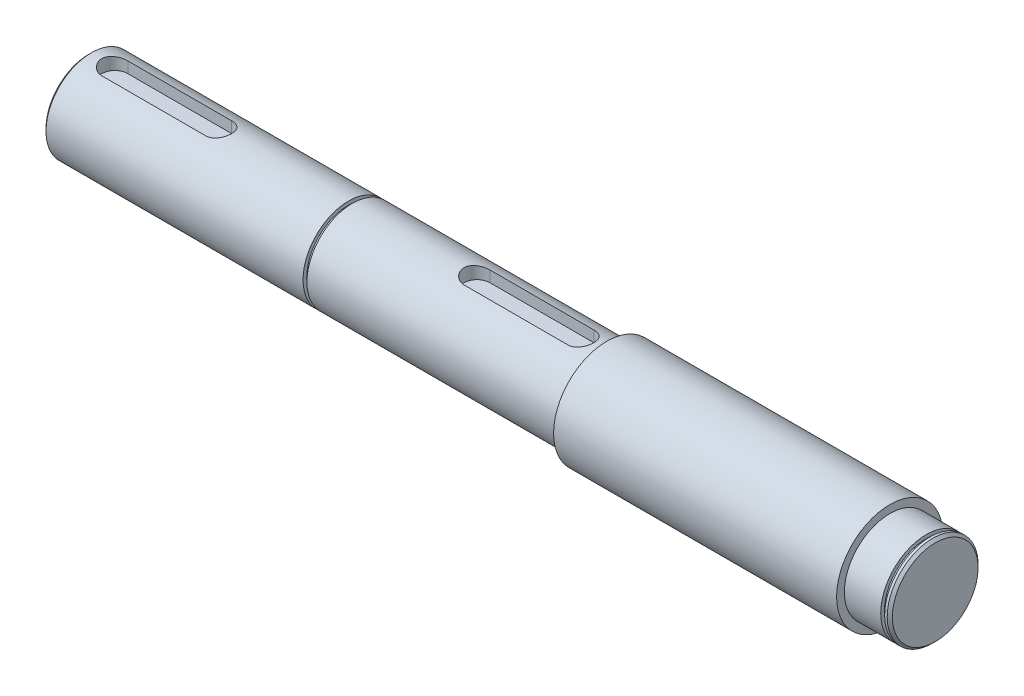
SolidWorks part; units mm, degrees
material "1.0050 (E295)"
ref_plane "Front Plane" through (0, 0, 0) normal (0, 0, 1) x (1, 0, 0)
ref_plane "Top Plane" through (0, 0, 0) normal (0, 1, 0) x (1, 0, 0)
ref_plane "Right Plane" through (0, 0, 0) normal (1, 0, 0) x (0, 0, -1)
sketch "Sketch1" plane through (0, 0, 0) normal (0, 0, 1) x (1, 0, 0)
  line L0 (0, 0) -> (326, 0)
  line L1 (0, 0) -> (0, 16.5)
  line L2 (1, 17.5) -> (100, 17.5)
  line L3 (100, 17.5) -> (100, 16.1)
  line L4 (100, 16.1) -> (101.5, 16.1)
  line L5 (101.5, 16.1) -> (101.5, 17.5)
  line L6 (101.5, 17.5) -> (199.5, 17.5)
  line L7 (326, 16.5) -> (326, 0)
  line L8 (0, 16.5) -> (1, 17.5)
  line L9 (199.5, 17.5) -> (199.5, 20.5)
  line L10 (199.5, 20.5) -> (308.5, 20.5)
  line L11 (308.5, 20.5) -> (308.5, 17.5)
  line L12 (308.5, 17.5) -> (322.5, 17.5)
  line L13 (325, 17.5) -> (326, 16.5)
  line L14 (324, 17.5) -> (324, 16.1)
  line L15 (324, 16.1) -> (322.5, 16.1)
  line L16 (322.5, 16.1) -> (322.5, 17.5)
  line L17 (324, 17.5) -> (325, 17.5)
  point P8 (0, 17.5)
  point P9 (326, 17.5)
  point P12 (101.5, 16.8)
  point P20 (169.5, 17.5)
  point P23 (109.5, 17.5)
  dimension "D1" = 17.5
  dimension "D2" = 100
  dimension "D3" = 16.1
  dimension "D5" = 1.5
  dimension "D6" = 109
  dimension "D7" = 30
  dimension "D8" = 14
  dimension "D9" = 3
  dimension "D10" = 1.5
  dimension "D11" = 16.1
  dimension "D13" = 2
  dimension "D14" = 8
  dimension "D15" = 60
revolve "Revolve1" add sketch "Sketch1" angle 360 about L0
ref_plane "Plane1" through (0, 17.5, 0) normal (0, 1, 0) x (1, 0, 0)
sketch "Sketch2" plane through (0, 17.5, 0) normal (0, 1, 0) x (1, 0, 0)
  line L0 (0, 0) -> (199.5, 0) construction
  line L1 (199.5, 17.5) -> (199.5, -17.5) construction
  line L2 (199.5, 20.5) -> (199.5, -20.5) construction
  line L3 (189.5, 0) -> (149.5, 0) construction
  line L4 (189.5, -5) -> (149.5, -5)
  line L5 (189.5, 5) -> (149.5, 5)
  arc A0 (189.5, -5) -> (189.5, 5) centre (189.5, 0) ccw
  arc A1 (149.5, 5) -> (149.5, -5) centre (149.5, 0) ccw
  point P5 (139.5, 0)
  point P10 (169.5, 0)
  point P15 (194.5, 0)
  point P16 (144.5, 0)
  dimension "D2" = 50
  dimension "D1" = 60
  dimension "D3" = 5
  dimension "D4" = 10
extrude "Cut-Extrude1" cut sketch "Sketch2" against normal blind 5
sketch "Sketch3" plane through (0, 17.5, 0) normal (0, 1, 0) x (1, 0, 0)
  line L0 (0, 0) -> (100, 0) construction
  line L1 (100, -17.5) -> (100, 17.5) construction
  line L2 (189.5, 5) -> (149.5, 5)
  line L3 (149.5, -5) -> (189.5, -5)
  line L4 (189.5, 5) -> (149.5, 5)
  line L5 (149.5, -5) -> (189.5, -5)
  line L6 (10, 0) -> (50, 0) construction
  line L7 (10, 5) -> (50, 5)
  line L8 (10, -5) -> (50, -5)
  line L9 (0, 16.5) -> (0, -16.5) construction
  arc A0 (10, 5) -> (10, -5) centre (10, 0) ccw
  arc A1 (50, -5) -> (50, 5) centre (50, 0) ccw
  arc A2 (189.5, -5) -> (189.5, 5) centre (189.5, 0) ccw
  arc A3 (149.5, 5) -> (149.5, -5) centre (149.5, 0) ccw
  arc A4 (189.5, -5) -> (189.5, 5) centre (189.5, 0) ccw
  arc A5 (149.5, 5) -> (149.5, -5) centre (149.5, 0) ccw
  point P13 (30, 0)
  dimension "D6" = 10
  dimension "D2" = 40
  dimension "D3" = 10
  dimension "D4" = 40
  dimension "D5" = 10
  dimension "D1" = 0
extrude "Cut-Extrude2" cut sketch "Sketch3" against normal blind 5
